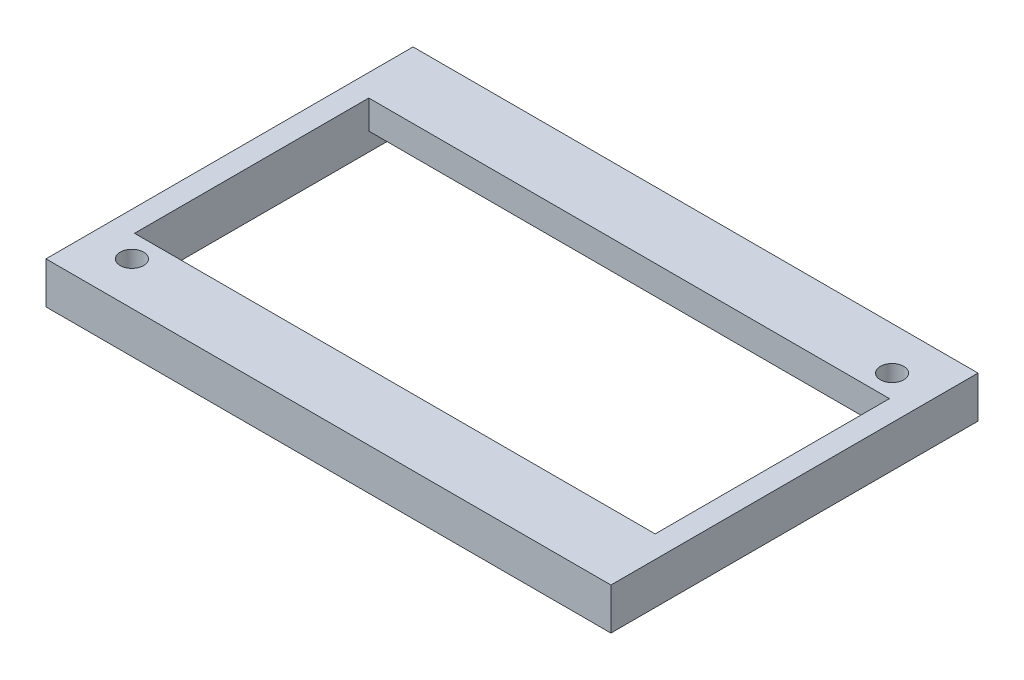
SolidWorks part; units mm, degrees
ref_plane "Front Plane" through (0, 0, 0) normal (0, 0, 1) x (1, 0, 0)
ref_plane "Top Plane" through (0, 0, 0) normal (0, 1, 0) x (1, 0, 0)
ref_plane "Right Plane" through (0, 0, 0) normal (1, 0, 0) x (0, 0, -1)
sketch "Sketch1" plane through (0, 0, 0) normal (0, 1, 0) x (1, 0, 0)
  line L1 (54.25, -35.25) -> (-54.25, -35.25)
  line L2 (54.25, -35.25) -> (54.25, 35.25)
  line L3 (54.25, 35.25) -> (-54.25, 35.25)
  line L4 (-54.25, -35.25) -> (-54.25, 35.25)
  line L5 (54.25, -35.25) -> (-54.25, 35.25) construction
  line L6 (54.25, 35.25) -> (-54.25, -35.25) construction
  point P0 (0, 0)
  dimension "D1" = 108.5
  dimension "D2" = 70.5
extrude "Boss-Extrude1" add sketch "Sketch1" along normal blind 8
sketch "Sketch2" plane through (0, 8, 0) normal (0, 1, 0) x (1, 0, 0)
  line L1 (50, -22.5) -> (-50, -22.5)
  line L2 (50, -22.5) -> (50, 22.5)
  line L3 (50, 22.5) -> (-50, 22.5)
  line L4 (-50, -22.5) -> (-50, 22.5)
  line L5 (50, -22.5) -> (-50, 22.5) construction
  line L6 (50, 22.5) -> (-50, -22.5) construction
  point P0 (0, 0)
  dimension "D1" = 45
  dimension "D2" = 100
sketch "Sketch3" plane through (0, 0, 0) normal (0, -1, 0) x (1, 0, 0)
  line L0 (-54.25, 35.25) -> (54.25, 35.25) construction
  line L1 (51.25, -32.25) -> (-51.25, -32.25)
  line L2 (51.25, -32.25) -> (51.25, 32.25)
  line L3 (51.25, 32.25) -> (-51.25, 32.25)
  line L4 (-51.25, -32.25) -> (-51.25, 32.25)
  line L5 (51.25, -32.25) -> (-51.25, 32.25) construction
  line L6 (51.25, 32.25) -> (-51.25, -32.25) construction
  line L7 (-54.25, -35.25) -> (-54.25, 35.25) construction
  point P1 (0, 0)
  dimension "D1" = 3
  dimension "D2" = 3
extrude "Boss-Extrude2" add sketch "Sketch3" along normal blind 1
extrude "Cut-Extrude2" cut sketch "Sketch2" against normal through all contours L2 L3 L4 L1
sketch "Sketch4" plane through (0, -1, 0) normal (0, -1, 0) x (1, 0, 0)
  line L0 (-51.25, -32.25) -> (51.25, -32.25) construction
  line L1 (50, -30.25) -> (-50, -30.25)
  line L2 (50, -30.25) -> (50, 30.25)
  line L3 (50, 30.25) -> (-50, 30.25)
  line L4 (-50, -30.25) -> (-50, 30.25)
  line L5 (50, -30.25) -> (-50, 30.25) construction
  line L6 (50, 30.25) -> (-50, -30.25) construction
  line L8 (-50, 22.5) -> (-50, -22.5) construction
  point P0 (0, 0)
  dimension "D1" = 2
extrude "Cut-Extrude3" cut sketch "Sketch4" against normal blind 3.5
sketch "Sketch8" plane through (0, 8, 0) normal (0, 1, 0) x (1, 0, 0)
  line L0 (-54.25, 35.25) -> (-54.25, -35.25) construction
  line L1 (-54.25, -35.25) -> (54.25, -35.25) construction
  line L2 (54.25, 35.25) -> (-54.25, 35.25) construction
  line L4 (54.25, -35.25) -> (54.25, 35.25) construction
  circle A0 centre (-46, -27) radius 2.25
  circle A1 centre (46, 27) radius 2.25
  dimension "D1" = 4.5
  dimension "D4" = 4.5
  dimension "D2" = 6
  dimension "D3" = 6
  dimension "D5" = 8.25
  dimension "D6" = 8.25
extrude "Cut-Extrude6" cut sketch "Sketch8" against normal through all
